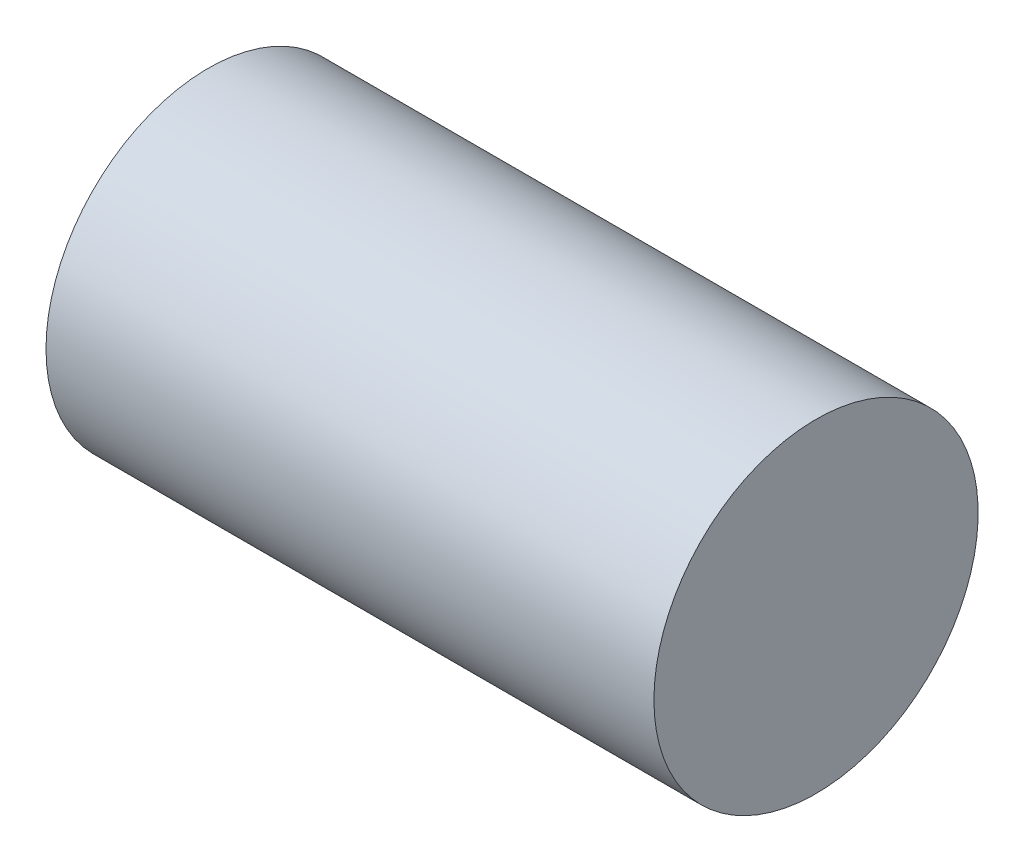
SolidWorks part; units mm, degrees
ref_plane "Front Plane" through (0, 0, 0) normal (0, 0, 1) x (1, 0, 0)
ref_plane "Top Plane" through (0, 0, 0) normal (0, 1, 0) x (1, 0, 0)
ref_plane "Right Plane" through (0, 0, 0) normal (1, 0, 0) x (0, 0, -1)
sketch "Sketch1" plane through (-162, 0, 0) normal (-1, 0, 0) x (0, 0, 1)
  circle A0 centre (0, 0) radius 8
extrude "Boss-Extrude1" add sketch "Sketch1" along normal blind 30
